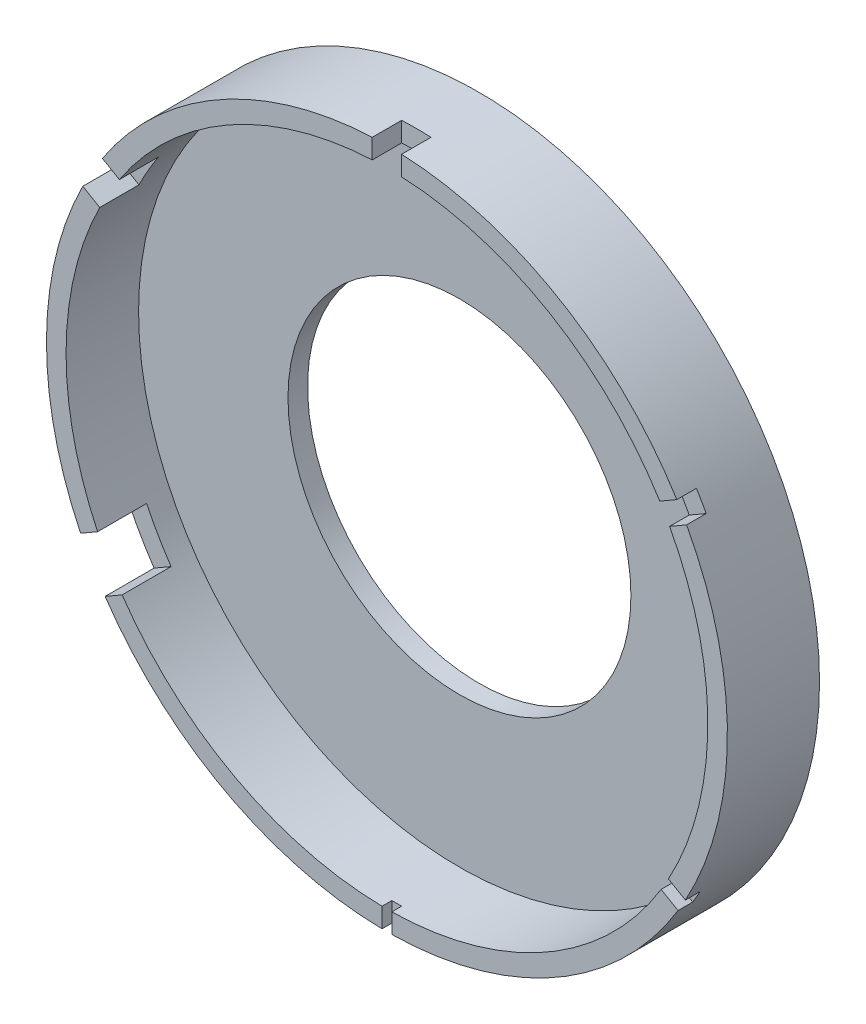
SolidWorks part; units mm, degrees
ref_plane "Plan de face" through (0, 0, 0) normal (0, 0, 1) x (1, 0, 0)
ref_plane "Plan de dessus" through (0, 0, 0) normal (0, 1, 0) x (1, 0, 0)
ref_plane "Plan de droite" through (0, 0, 0) normal (1, 0, 0) x (0, 0, -1)
sketch "Esquisse1" plane through (0, 0, 0) normal (0, 0, 1) x (1, 0, 0)
  circle A0 centre (0, 0) radius 34.75
  circle A1 centre (0, 0) radius 32.75
  dimension "D1" = 69.5
  dimension "D2" = 2
extrude "Boss.-Extru.1" add sketch "Esquisse1" along normal blind 9.4
sketch "Esquisse2" plane through (0, 0, 0) normal (0, 0, -1) x (-1, 0, 0)
  circle A0 centre (0, 0) radius 34.75
  circle A1 centre (0, 0) radius 34.75 construction
extrude "Boss.-Extru.2" add sketch "Esquisse2" against normal blind 2
sketch "Esquisse3" plane through (0, 0, 9.4) normal (0, 0, 1) x (1, 0, 0)
  line L0 (0, -32.75) -> (0, 0) construction
  line L1 (-0.5, -32.7462) -> (-0.5, -35.2462)
  line L2 (-0.5, -35.2462) -> (0.5, -35.2462)
  line L3 (-0.5, -32.7462) -> (0.5, -32.7462)
  line L4 (0, -35.2462) -> (0, -32.7462) construction
  line L5 (0.5, -32.7462) -> (0.5, -35.2462)
  circle A0 centre (0, 0) radius 32.75 construction
  circle A1 centre (0, 0) radius 32.75 construction
  dimension "D1" = 1
  dimension "D2" = 2.5
extrude "Enlèv. mat.-Extru.1" cut sketch "Esquisse3" against normal blind 1
sketch "Esquisse4" plane through (0, 0, 9.4) normal (0, 0, 1) x (1, 0, 0)
  line L0 (0, 0) -> (0, -32.75) construction
  line L1 (0, 0) -> (30.0944, -17.375) construction
  line L2 (28.7299, -15.7212) -> (27.9799, -17.0202)
  line L3 (27.9799, -17.0202) -> (30.145, -18.2702)
  line L4 (30.145, -18.2702) -> (30.895, -16.9712)
  line L5 (28.7299, -15.7212) -> (30.895, -16.9712)
  arc A0 (-0.5, -32.7462) -> (0.5, -32.7462) centre (0, 0) ccw construction
  arc A1 (0.5, -34.7464) -> (-0.5, -34.7464) centre (0, 0) ccw construction
  circle A2 centre (0, 0) radius 32.75 construction
  point P12 (0, 0)
  point P15 (27.4399, -17.8777)
  point P19 (30.52, -17.6207)
  point P20 (28.3549, -16.3707)
  dimension "D1" = 60
  dimension "D2" = 2.5
  dimension "D3" = 1.5
extrude "Enlèv. mat.-Extru.2" cut sketch "Esquisse4" against normal blind 1.5
sketch "Esquisse5" plane through (0, 0, 9.4) normal (0, 0, 1) x (1, 0, 0)
  line L0 (0, 0) -> (30.0944, -17.375) construction
  line L1 (0, 0) -> (30.0944, 17.375) construction
  line L2 (27.8491, 17.2334) -> (28.8491, 15.5013)
  line L3 (28.8491, 15.5013) -> (31.0142, 16.7513)
  line L4 (31.0142, 16.7513) -> (30.0142, 18.4834)
  line L5 (27.8491, 17.2334) -> (30.0142, 18.4834)
  arc A0 (29.7124, -18.0205) -> (30.4624, -16.7214) centre (0, 0) ccw construction
  arc A1 (30.4624, -16.7214) -> (-0.5, -34.7464) centre (0, 0) ccw construction
  circle A2 centre (0, 0) radius 32.75 construction
  point P12 (28.044, 16.1912)
  point P15 (28.8491, 15.5013)
  point P18 (0, 0)
  point P20 (30.5142, 17.6174)
  point P21 (28.3491, 16.3674)
  dimension "D1" = 60
  dimension "D2" = 2
  dimension "D3" = 2.5
extrude "Enlèv. mat.-Extru.3" cut sketch "Esquisse5" against normal blind 2
sketch "Esquisse6" plane through (0, 0, 9.4) normal (0, 0, 1) x (1, 0, 0)
  line L0 (0, 34.75) -> (0, 0) construction
  line L1 (-1.5, 32.7156) -> (1.5, 32.7156)
  line L2 (1.5, 32.7156) -> (1.5, 35.2156)
  line L3 (1.5, 35.2156) -> (-1.5, 35.2156)
  line L4 (-1.5, 32.7156) -> (-1.5, 35.2156)
  arc A0 (29.5819, 18.2338) -> (-0.5, -34.7464) centre (0, 0) ccw construction
  circle A1 centre (0, 0) radius 32.75 construction
  point P8 (1.25, 32.7261)
  point P13 (0, 0)
  point P15 (0, 35.2156)
  point P16 (0, 32.7156)
  dimension "D1" = 3
  dimension "D2" = 2.5
extrude "Enlèv. mat.-Extru.4" cut sketch "Esquisse6" against normal blind 3
sketch "Esquisse7" plane through (0, 0, 9.4) normal (0, 0, 1) x (1, 0, 0)
  line L0 (0, 0) -> (-30.0944, 17.375) construction
  line L1 (0, 0) -> (0, 34.75) construction
  line L2 (-29.3094, 14.6124) -> (-27.3094, 18.0765)
  line L3 (-27.3094, 18.0765) -> (-29.4745, 19.3265)
  line L4 (-29.4745, 19.3265) -> (-31.4745, 15.8624)
  line L5 (-29.3094, 14.6124) -> (-31.4745, 15.8624)
  arc A0 (-1.5, 34.7176) -> (-0.5, -34.7464) centre (0, 0) ccw construction
  arc A1 (1.5, 34.7176) -> (-1.5, 34.7176) centre (0, 0) ccw construction
  arc A2 (-1.5, 32.7156) -> (-0.5, -32.7462) centre (0, 0) ccw construction
  point P12 (-27.5882, 17.6481)
  point P19 (-30.4745, 17.5944)
  point P20 (-28.3094, 16.3444)
  dimension "D1" = 60
  dimension "D2" = 4
  dimension "D3" = 2.5
extrude "Enlèv. mat.-Extru.5" cut sketch "Esquisse7" against normal blind 4
sketch "Esquisse8" plane through (0, 0, 9.4) normal (0, 0, 1) x (1, 0, 0)
  line L0 (0, -32.75) -> (0, 0) construction
  line L1 (0, 0) -> (-30.0944, -17.375) construction
  line L2 (-27.0296, -18.4923) -> (-29.5296, -14.1622)
  line L3 (-29.5296, -14.1622) -> (-31.6946, -15.4122)
  line L4 (-31.6946, -15.4122) -> (-29.1946, -19.7423)
  line L5 (-27.0296, -18.4923) -> (-29.1946, -19.7423)
  arc A0 (-0.5, -32.7462) -> (0.5, -32.7462) centre (0, 0) ccw construction
  arc A1 (-31.0445, 15.6141) -> (-0.5, -34.7464) centre (0, 0) ccw construction
  circle A2 centre (0, 0) radius 32.75 construction
  point P13 (0, 0)
  point P15 (-29.5296, -14.1621)
  point P19 (-30.4446, -17.5772)
  point P20 (-28.2796, -16.3272)
  dimension "D1" = 60
  dimension "D2" = 5
  dimension "D3" = 2.5
extrude "Enlèv. mat.-Extru.6" cut sketch "Esquisse8" against normal blind 5
sketch "Esquisse9" plane through (0, 0, 2) normal (0, 0, 1) x (1, 0, 0)
  circle A0 centre (0, 0) radius 17.5
  dimension "D1" = 35
extrude "Enlèv. mat.-Extru.7" cut sketch "Esquisse9" against normal through all both and the other way through all
